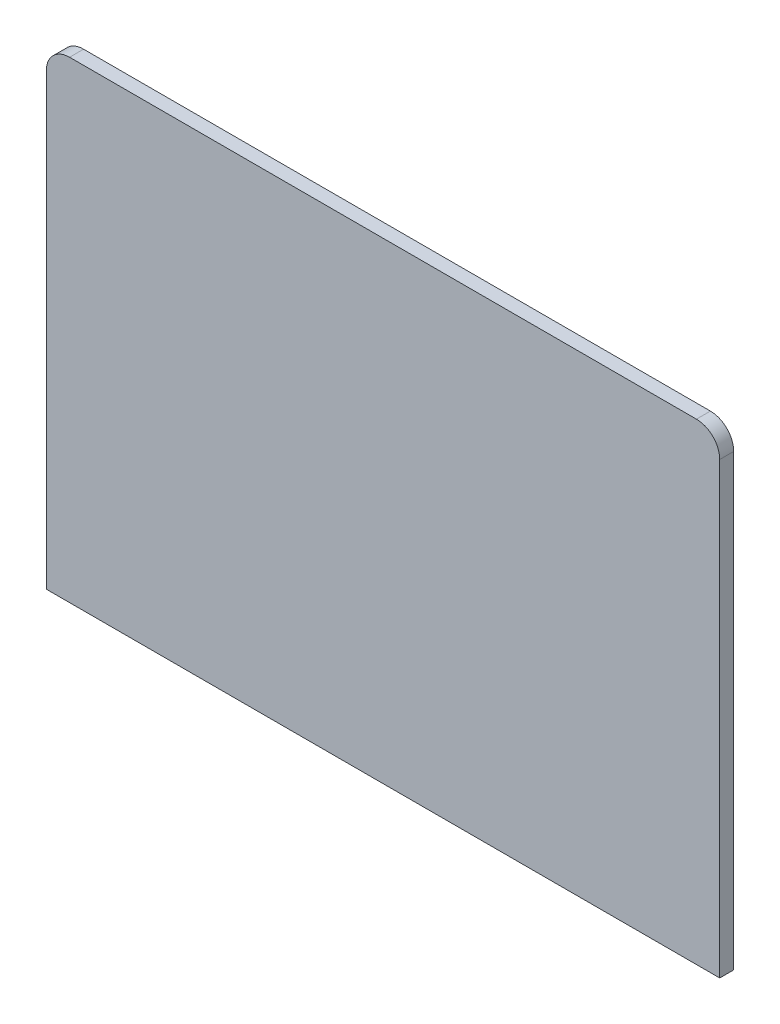
SolidWorks part; units mm, degrees
ref_plane "Front Plane" through (0, 0, 0) normal (0, 0, 1) x (1, 0, 0)
ref_plane "Top Plane" through (0, 0, 0) normal (0, 1, 0) x (1, 0, 0)
ref_plane "Right Plane" through (0, 0, 0) normal (1, 0, 0) x (0, 0, -1)
sketch "Sketch1" plane through (0, 0, 0) normal (0, 0, 1) x (1, 0, 0)
  line L1 (0, 0) -> (144.5, 0)
  line L2 (0, 0) -> (0, 101.35)
  line L3 (0, 101.35) -> (144.5, 101.35)
  line L4 (144.5, 0) -> (144.5, 101.35)
  dimension "D1" = 101.35
  dimension "D2" = 144.5
extrude "Boss-Extrude1" add sketch "Sketch1" along normal blind 3
fillet "Fillet1" radius 5 2 edges at (144.5, 101.35, 1.5) (0, 101.35, 1.5)
